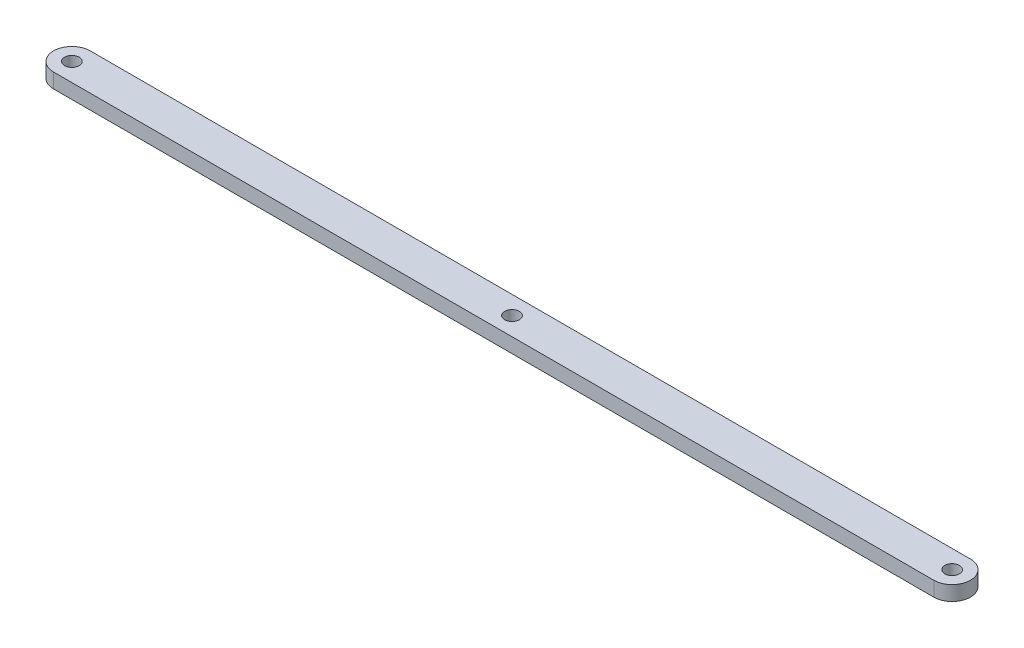
SolidWorks part; units mm, degrees
ref_plane "Front Plane" through (0, 0, 0) normal (0, 0, 1) x (1, 0, 0)
ref_plane "Top Plane" through (0, 0, 0) normal (0, 1, 0) x (1, 0, 0)
ref_plane "Right Plane" through (0, 0, 0) normal (1, 0, 0) x (0, 0, -1)
sketch "Sketch1" plane through (0, 0, 0) normal (0, 1, 0) x (1, 0, 0)
  line L0 (-60, 0) -> (60, 0) construction
  line L1 (-60, 2.5) -> (60, 2.5)
  line L2 (-60, -2.5) -> (60, -2.5)
  arc A0 (-60, 2.5) -> (-60, -2.5) centre (-60, 0) ccw
  arc A1 (60, -2.5) -> (60, 2.5) centre (60, 0) ccw
  circle A2 centre (60, 0) radius 1
  circle A3 centre (-60, 0) radius 1
  circle A4 centre (0, 0) radius 1
  point P3 (0, 0)
  dimension "D3" = 2
  dimension "D4" = 2.5
  dimension "D5" = 2
  dimension "D2" = 2
  dimension "D1" = 120
  dimension "D12" = 60
extrude "Boss-Extrude1" add sketch "Sketch1" along normal blind 2
